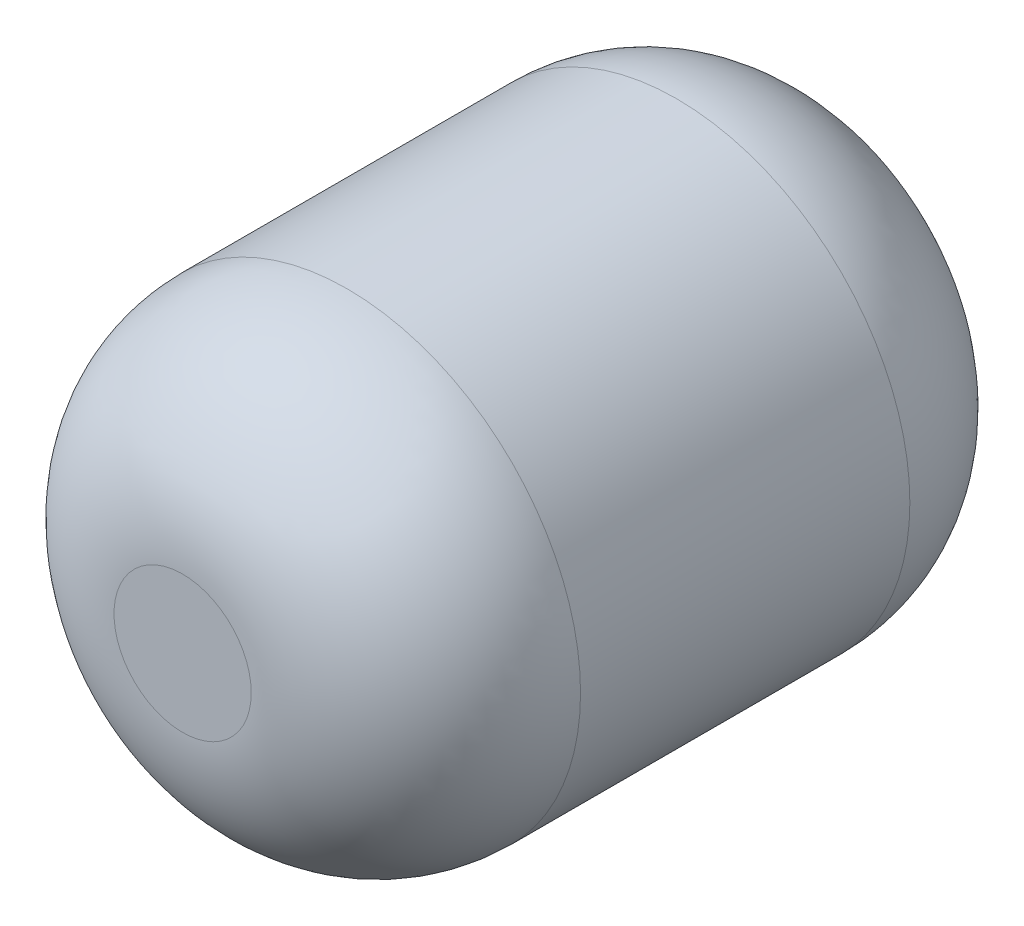
SolidWorks part; units mm, degrees
ref_plane "Front Plane" through (0, 0, 0) normal (0, 0, 1) x (1, 0, 0)
ref_plane "Top Plane" through (0, 0, 0) normal (0, 1, 0) x (1, 0, 0)
ref_plane "Right Plane" through (0, 0, 0) normal (1, 0, 0) x (0, 0, -1)
sketch "Sketch1" plane through (0, 0, 0) normal (0, 0, 1) x (1, 0, 0)
  circle A0 centre (0, 0) radius 107.95
  dimension "D1" = 215.9
extrude "Boss-Extrude1" add sketch "Sketch1" along normal blind 304.8
fillet "Fillet1" radius 76.2 2 edges at (107.95, 0, 0) (107.95, 0, 304.8)
sketch "Sketch2" plane through (0, 0, 0) normal (1, 0, 0) x (0, 0, -1)
  line L0 (-228.6, 107.95) -> (-304.8, 107.95) construction
  line L1 (-228.6, -107.95) -> (-228.6, 107.95) construction
  line L2 (-304.8, 107.95) -> (-304.8, 6.35) construction
  line L3 (-304.8, 31.75) -> (-304.8, -31.75) construction
  line L4 (-228.6, 107.95) -> (-304.8, 6.35) construction
  line L5 (-76.2, 107.95) -> (0, 107.95) construction
  line L6 (-76.2, 107.95) -> (-76.2, -107.95) construction
  line L7 (0, 107.95) -> (0, 6.35) construction
  line L8 (0, -31.75) -> (0, 31.75) construction
  line L9 (0, 6.35) -> (-76.2, 107.95) construction
  point P9 (-304.8, 57.15)
  point P12 (0, 57.15)
  dimension "D1" = 101.6
ref_plane "Plane1" through (0, -107.95, 0) normal (0, 1, 0) x (1, 0, 0)
sketch "Sketch3" plane through (0, -107.95, 0) normal (0, 1, 0) x (1, 0, 0)
  point P0 (0, -152.4)
ref_plane "Plane2" through (0, 95.25, 0) normal (0, 1, 0) x (1, 0, 0)
sketch "Sketch5" plane through (0, 95.25, 0) normal (0, 1, 0) x (1, 0, 0)
  point P0 (0, -152.4)
sketch3d "3DSketch1"
  line L0 (0, 6.35, 304.8) -> (0, 6.35, 0)
sketch3d "3DSketch2"
  line L0 (0, 95.25, 152.4) -> (0, -107.95, 152.4)
